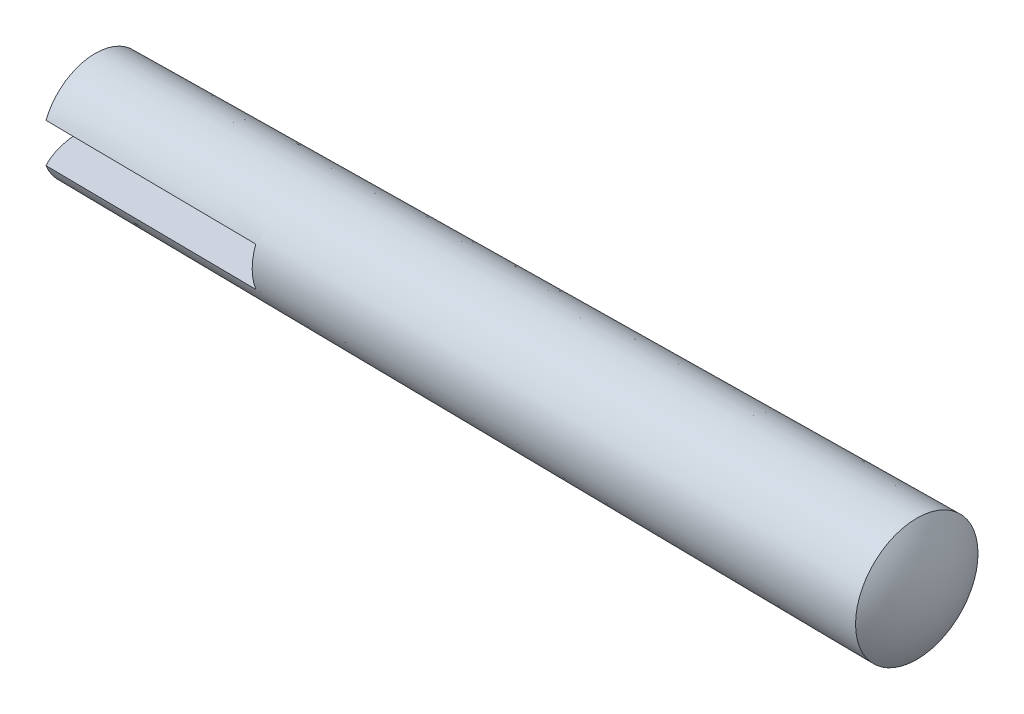
SolidWorks part; units mm, degrees
ref_plane "Plane1" through (0, 0, 0) normal (0, 0, 1) x (1, 0, 0)
ref_plane "Plane2" through (0, 0, 0) normal (0, 1, 0) x (1, 0, 0)
ref_plane "Plane3" through (0, 0, 0) normal (1, 0, 0) x (0, 0, -1)
sketch "Clipboard" plane through (0, 0, 0) normal (0, 0, 1) x (1, 0, 0)
  line L0 (0, 0) -> (10, 0)
  dimension "D1" = 10
sketch "BodySke" plane through (0, 0, 0) normal (0, 0, 1) x (1, 0, 0)
  line L0 (-0.6699, 0) -> (210, 0) construction
  line L1 (60, 0) -> (-0.6699, 0) construction
  line L2 (0, 2.5) -> (38.74, 2.8874)
  line L3 (0, 0) -> (0, 10) construction
  line L4 (-0.6699, 0) -> (39.658, 0)
  arc A0 (0, 2.5) -> (-0.6699, 0) centre (4.3301, 0) ccw
  arc A1 (38.74, 2.8874) -> (39.658, 0) centre (34.658, 0) cw
  dimension "D1" = 5
  dimension "D3" = 5
  dimension "D2" = 0.573
  dimension "Length" = 38.74
  dimension "Diameter" = 5
revolve "Body" add sketch "BodySke" angle 360 about L0
sketch "SplSke" plane through (0, 0, 0) normal (1, 0, 0) x (0, 0, -1)
  line L0 (0, 2) -> (0, -2) construction
  line L1 (2.8874, -0.9251) -> (-2.8874, -0.9251)
  line L2 (2.8874, -0.9251) -> (2.8874, 0.9251)
  line L3 (2.8874, 0.9251) -> (-2.8874, 0.9251)
  line L4 (-2.8874, -0.9251) -> (-2.8874, 0.9251)
  line L5 (2, 0) -> (-2, 0) construction
  circle A0 centre (0, 0) radius 2.8874 construction
  dimension "Width" = 1.8502
extrude "Split" cut sketch "SplSke" along normal blind 10 and the other way through all
equation "\"D1@BodySke\" = \"Diameter@BodySke\""
equation "\"D3@BodySke\" = \"Diameter@BodySke\""
